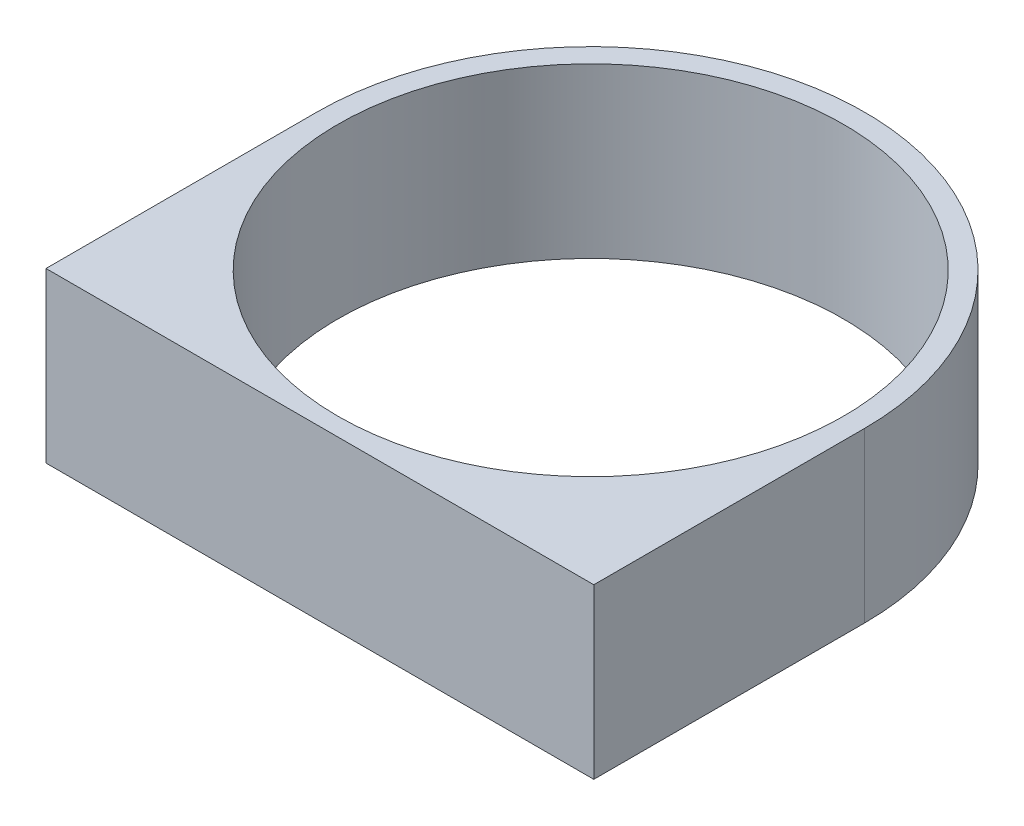
SolidWorks part; units mm, degrees
ref_plane "Front Plane" through (0, 0, 0) normal (0, 0, 1) x (1, 0, 0)
ref_plane "Top Plane" through (0, 0, 0) normal (0, 1, 0) x (1, 0, 0)
ref_plane "Right Plane" through (0, 0, 0) normal (1, 0, 0) x (0, 0, -1)
sketch "Sketch1" plane through (0, 0, 0) normal (0, 1, 0) x (1, 0, 0)
  line L0 (-3.25, 0) -> (-3.25, -3.2134)
  line L2 (3.25, -3.2134) -> (3.25, 0)
  line L3 (0.25, -3.2134) -> (-3.25, -3.2134)
  line L4 (0.25, -3.2134) -> (3.25, -3.2134)
  circle A0 centre (0, 0) radius 3
  arc A1 (3.25, 0) -> (-3.25, 0) centre (0, 0) ccw
  dimension "D1" = 6
  dimension "D2" = 6.5
extrude "Boss-Extrude1" add sketch "Sketch1" along normal blind 2
sketch "Sketch2" plane through (0, 2, 0) normal (0, 1, 0) x (1, 0, 0)
